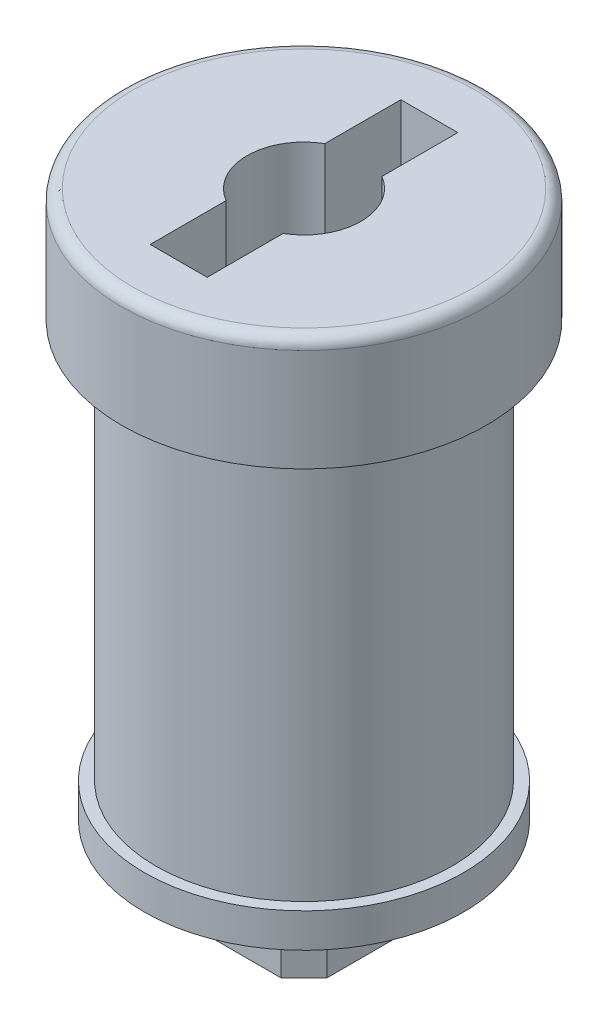
SolidWorks part; units mm, degrees
ref_plane "Front Plane" through (0, 0, 0) normal (0, 0, 1) x (1, 0, 0)
ref_plane "Top Plane" through (0, 0, 0) normal (0, 1, 0) x (1, 0, 0)
ref_plane "Right Plane" through (0, 0, 0) normal (1, 0, 0) x (0, 0, -1)
sketch "Sketch1" plane through (0, 0, 0) normal (0, 0, 1) x (1, 0, 0)
  line L0 (0, 0) -> (7, 0)
  line L1 (7, 0) -> (7, 1.5)
  line L2 (7, 1.5) -> (6.5, 1.5)
  line L3 (6.5, 1.5) -> (6.5, 19)
  line L4 (6.5, 19) -> (8, 19)
  line L5 (8, 19) -> (8, 24)
  line L6 (8, 24) -> (0, 24)
  line L7 (0, 24) -> (0, 0)
  dimension "D1" = 24
  dimension "D2" = 5
  dimension "D3" = 8
  dimension "D4" = 6.5
  dimension "D5" = 7
  dimension "D6" = 1.5
revolve "Revolve1" add sketch "Sketch1" angle 360 about L7
sketch "Sketch2" plane through (0, 24, 0) normal (0, 1, 0) x (1, 0, 0)
  line L1 (-1.25, -5.5) -> (1.25, -5.5)
  line L2 (-1.25, -5.5) -> (-1.25, 5.5)
  line L3 (-1.25, 5.5) -> (1.25, 5.5)
  line L4 (1.25, -5.5) -> (1.25, 5.5)
  line L5 (-1.25, -5.5) -> (1.25, 5.5) construction
  line L6 (-1.25, 5.5) -> (1.25, -5.5) construction
  point P0 (0, 0)
  dimension "D1" = 2.5
  dimension "D2" = 11
extrude "Cut-Extrude1" cut sketch "Sketch2" against normal blind 10
sketch "Sketch3" plane through (0, 24, 0) normal (0, 1, 0) x (1, 0, 0)
  circle A0 centre (0, 0) radius 2.5
  dimension "D1" = 5
extrude "Cut-Extrude2" cut sketch "Sketch3" against normal blind 10
fillet "Fillet1" radius 0.5 1 edges at (0, 24, 8)
sketch "Sketch4" plane through (0, 0, 0) normal (0, -1, 0) x (1, 0, 0)
  line L1 (-4, -4) -> (4, -4)
  line L2 (-4, -4) -> (-4, 4)
  line L3 (-4, 4) -> (4, 4)
  line L4 (4, -4) -> (4, 4)
  line L5 (-4, -4) -> (4, 4) construction
  line L6 (-4, 4) -> (4, -4) construction
  point P0 (0, 0)
  dimension "D1" = 8
  dimension "D2" = 8
extrude "Boss-Extrude1" add sketch "Sketch4" along normal blind 2.5
chamfer "Chamfer1" distance 1 angle 45 4 edges at (4, -1.25, 4) (4, -1.25, -4) (-4, -1.25, -4) (-4, -1.25, 4)
hole_wizard "M5 Tapped Hole1" positions "Sketch6" profile "Sketch7" tap size "M5" standard "ISO"
sketch "Sketch6" plane through (0, -2.5, 0) normal (0, -1, 0) x (-1, 0, 0)
  point P0 (0, 0)
sketch "Sketch7" plane through (0, -2.5, 0) normal (1, 0, 0) x (0, 0, -1)
  line L0 (0, 0) -> (0, 9.2618)
  line L1 (0, 9.2618) -> (2.1, 8)
  line L2 (2.1, 8) -> (2.1, 0)
  line L5 (2.1, 0) -> (0, 0)
  line L10 (0, 9.2618) -> (-2.1, 8) construction
  line L11 (0, -6.35) -> (0, 107.95) construction
  dimension "Tap Drill Dia." = 4.2
  dimension "Tap Drill Depth" = 8
  dimension "Drill Angle" = 118
cosmetic thread "Hole Thread1" parameters "D1"=6, "D2"=5
